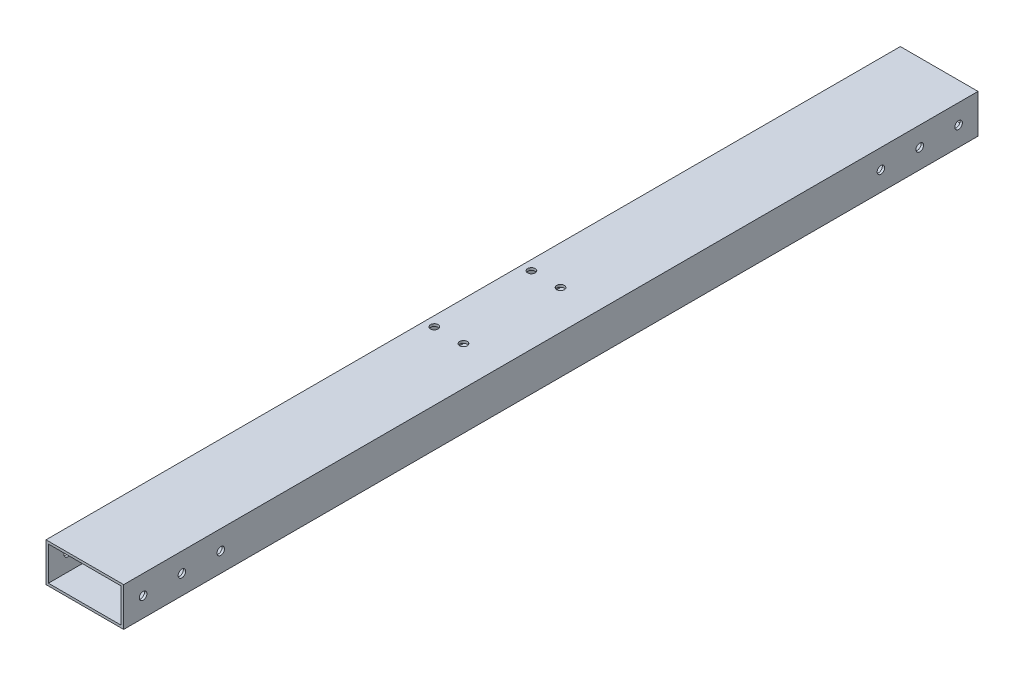
SolidWorks part; units mm, degrees
ref_plane "Front Plane" through (0, 0, 0) normal (0, 0, 1) x (1, 0, 0)
ref_plane "Top Plane" through (0, 0, 0) normal (0, 1, 0) x (1, 0, 0)
ref_plane "Right Plane" through (0, 0, 0) normal (1, 0, 0) x (0, 0, -1)
sketch "Sketch1" plane through (0, 0, 0) normal (0, 0, 1) x (1, 0, 0)
  line L1 (-25.4, -12.7) -> (25.4, -12.7)
  line L2 (-25.4, -12.7) -> (-25.4, 12.7)
  line L3 (-25.4, 12.7) -> (25.4, 12.7)
  line L4 (25.4, -12.7) -> (25.4, 12.7)
  line L5 (-25.4, -12.7) -> (25.4, 12.7) construction
  line L6 (-25.4, 12.7) -> (25.4, -12.7) construction
  point P0 (0, 0)
  dimension "D1" = 50.8
  dimension "D2" = 25.4
extrude "Boss-Extrude1" add sketch "Sketch1" along normal mid plane 558.8
shell "Shell1" thickness 1.5875
sketch "Sketch3" plane through (0, 0, 0) normal (1, 0, 0) x (0, 0, -1)
  line L0 (-279.4, -12.7) -> (-279.4, 12.7) construction
  line L1 (0, 12.7) -> (0, -12.7) construction
  line L2 (-279.4, 12.7) -> (279.4, 12.7) construction
  line L3 (-279.4, -12.7) -> (279.4, -12.7) construction
  circle A0 centre (-266.7, 0) radius 2.4892
  circle A1 centre (-241.3, 0) radius 2.4892
  circle A2 centre (-215.9, 0) radius 2.4892
  circle A3 centre (215.9, 0) radius 2.4892
  circle A4 centre (241.3, 0) radius 2.4892
  circle A5 centre (266.7, 0) radius 2.4892
  dimension "D2" = 4.9784
  dimension "D1" = 12.7
  dimension "D3" = 25.4
  dimension "D4" = 25.4
  dimension "D5" = 12.7
extrude "Cut-Extrude1" cut sketch "Sketch3" against normal through all both and the other way through all
sketch "Sketch4" plane through (0, 0, 0) normal (0, 1, 0) x (1, 0, 0)
  line L1 (-25.4, -279.4) -> (-25.4, 279.4) construction
  circle A0 centre (0, -31.75) radius 2.4892
  circle A1 centre (-19.05, -31.75) radius 2.4892
  circle A2 centre (0, 31.75) radius 2.4892
  circle A3 centre (-19.05, 31.75) radius 2.4892
  point P8 (-18.2943, -31.75)
  point P11 (0, -31.75)
  point P12 (0, -31.75)
  point P13 (0, 0)
  point P14 (0, 0)
  dimension "D1" = 4.9784
  dimension "D3" = 19.05
  dimension "D4" = 31.75
  dimension "D2" = 6.35
  dimension "D5" = 63.5
extrude "Cut-Extrude2" cut sketch "Sketch4" against normal through all both and the other way through all
equation "\"D4@Sketch3\"=\"D3@Sketch3\""
equation "\"D4@Sketch4\"=1.5-.25"
